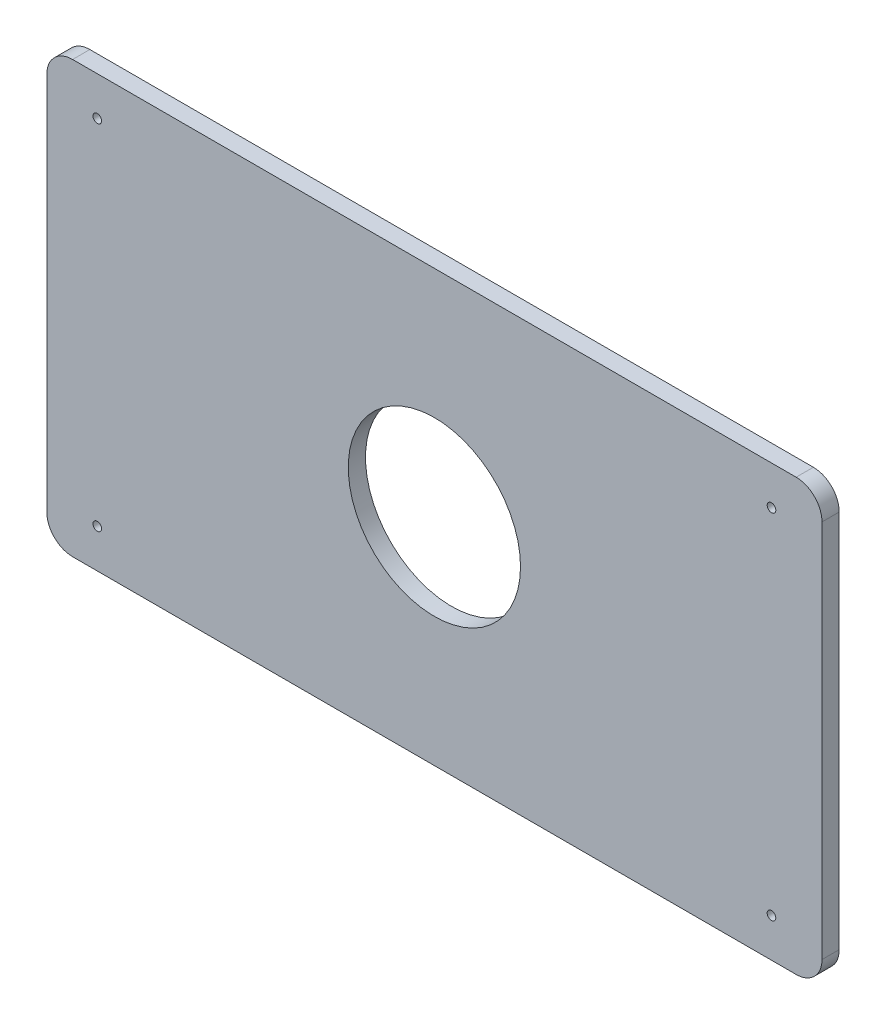
SolidWorks part; units mm, degrees
ref_plane "Alzado" through (0, 0, 0) normal (0, 0, 1) x (1, 0, 0)
ref_plane "Planta" through (0, 0, 0) normal (0, 1, 0) x (1, 0, 0)
ref_plane "Vista lateral" through (0, 0, 0) normal (1, 0, 0) x (0, 0, -1)
sketch "Croquis1" plane through (0, 0, 0) normal (0, 0, 1) x (1, 0, 0)
  line L0 (415, 125) -> (450, 125) construction
  line L1 (15, 0) -> (435, 0)
  line L2 (0, 15) -> (0, 235)
  line L3 (15, 250) -> (435, 250)
  line L4 (450, 15) -> (450, 235)
  line L9 (110, 250) -> (110, 0) construction
  line L16 (225, 250) -> (225, 0) construction
  line L17 (0, 125) -> (450, 125) construction
  line L67 (315, 0) -> (325.0903, 0) construction
  arc A5 (435, 250) -> (450, 235) centre (435, 235) cw
  arc A6 (435, 0) -> (450, 15) centre (435, 15) ccw
  arc A7 (15, 0) -> (0, 15) centre (15, 15) cw
  arc A8 (0, 235) -> (15, 250) centre (15, 235) cw
  circle A34 centre (225, 125) radius 50
  point P29 (450, 0)
  point P32 (0, 0)
  point P35 (0, 250)
  point P46 (225, 125)
  dimension "D10" = 15
  dimension "D3" = 100
  dimension "D1" = 450
  dimension "D2" = 250
  dimension "D6" = 110
extrude "Saliente-Extruir1" add sketch "Croquis1" along normal blind 10
sketch "Croquis2" plane through (0, 0, 10) normal (0, 0, 1) x (1, 0, 0)
  line L0 (15, 15) -> (435, 235) construction
  line L1 (15, 235) -> (435, 15) construction
  line L2 (225, 125) -> (225, 250) construction
  line L3 (435, 250) -> (15, 250) construction
  line L4 (420.6818, 22.5) -> (420.6818, 227.5) construction
  circle A0 centre (420.6818, 22.5) radius 2.5
  circle A1 centre (420.6818, 227.5) radius 2.5
  circle A2 centre (29.3182, 227.5) radius 2.5
  circle A3 centre (29.3182, 22.5) radius 2.5
  dimension "D2" = 5
  dimension "D1" = 22.5
extrude "Cortar-Extruir1" cut sketch "Croquis2" against normal blind 10
